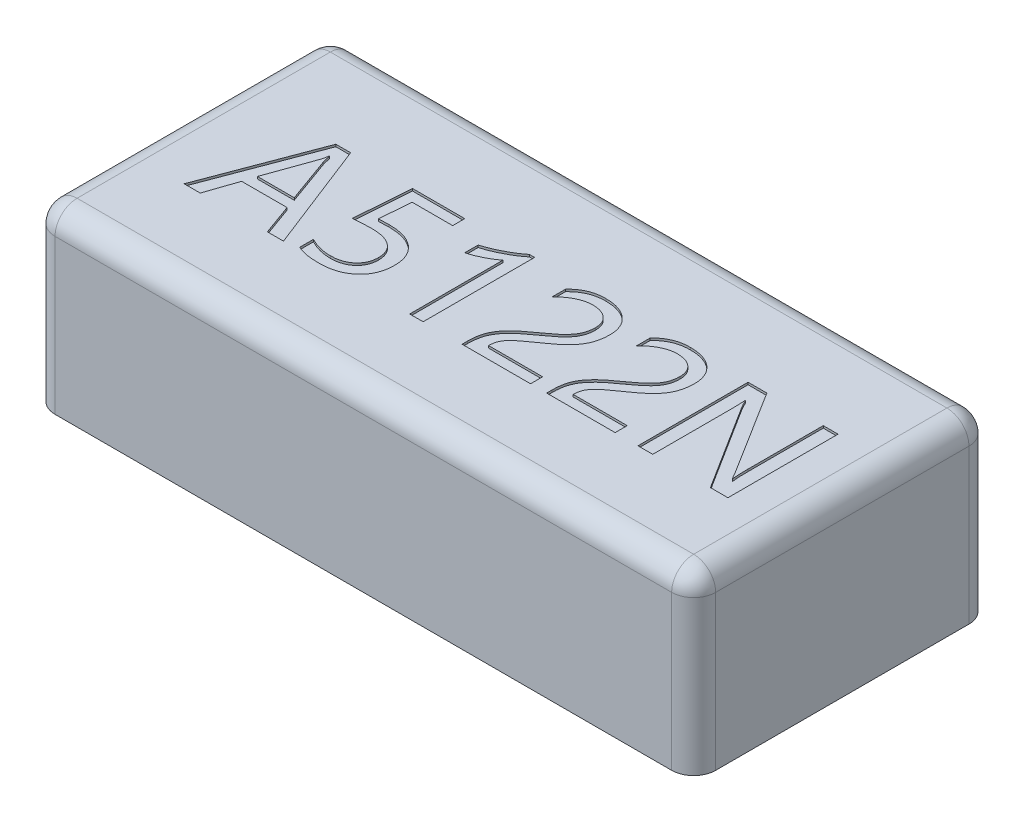
SolidWorks part; units mm, degrees
ref_plane "前视基准面" through (0, 0, 0) normal (0, 0, 1) x (1, 0, 0)
ref_plane "上视基准面" through (0, 0, 0) normal (0, 1, 0) x (1, 0, 0)
ref_plane "右视基准面" through (0, 0, 0) normal (1, 0, 0) x (0, 0, -1)
sketch "草图1" plane through (0, 0, 0) normal (0, 1, 0) x (1, 0, 0)
  line L1 (-1.5, -0.675) -> (1.5, -0.675)
  line L2 (-1.5, -0.675) -> (-1.5, 0.675)
  line L3 (-1.5, 0.675) -> (1.5, 0.675)
  line L4 (1.5, -0.675) -> (1.5, 0.675)
  line L5 (-1.5, -0.675) -> (1.5, 0.675) construction
  line L6 (-1.5, 0.675) -> (1.5, -0.675) construction
  point P0 (0, 0)
  dimension "D1" = 3
  dimension "D2" = 1.35
extrude "凸台-拉伸1" add sketch "草图1" along normal blind 0.8
sketch "草图2" plane through (0, 0.8, 0) normal (0, 1, 0) x (1, 0, 0)
  line L0 (-1.5, -0.675) -> (1.5, -0.675) construction
  line L1 (-1.5, 0.675) -> (-1.5, -0.675) construction
  text T0 "A5122N" font "微软雅黑" height 0.5
  dimension "D1" = 0.4
  dimension "D2" = 0.28
extrude "切除-拉伸1" cut sketch "草图2" against normal blind 0.01
fillet "圆角1" radius 0.1 8 edges at (1.5, 0.4, -0.675) (1.5, 0.4, 0.675) (-1.5, 0.4, -0.675) (-1.5, 0.4, 0.675) (1.5, 0.8, 0) (0, 0.8, -0.675) (-1.5, 0.8, 0) (0, 0.8, 0.675)
